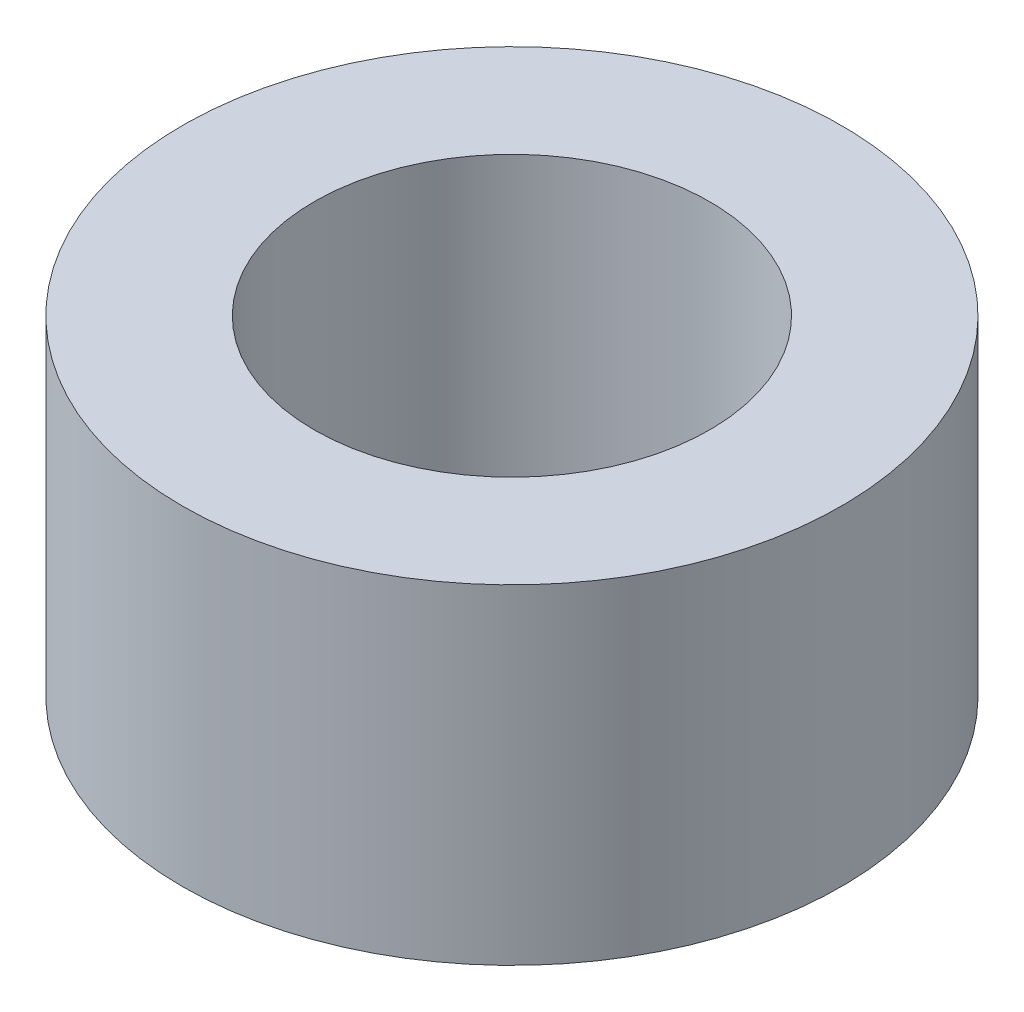
SolidWorks part; units mm, degrees
ref_plane "Front Plane" through (0, 0, 0) normal (0, 0, 1) x (1, 0, 0)
ref_plane "Top Plane" through (0, 0, 0) normal (0, 1, 0) x (1, 0, 0)
ref_plane "Right Plane" through (0, 0, 0) normal (1, 0, 0) x (0, 0, -1)
sketch "Sketch1" plane through (0, 0, 0) normal (0, 1, 0) x (1, 0, 0)
  circle A0 centre (0, 0) radius 3
  circle A1 centre (0, 0) radius 5
  dimension "D1" = 6
  dimension "D2" = 2
extrude "Boss-Extrude1" add sketch "Sketch1" along normal blind 5
